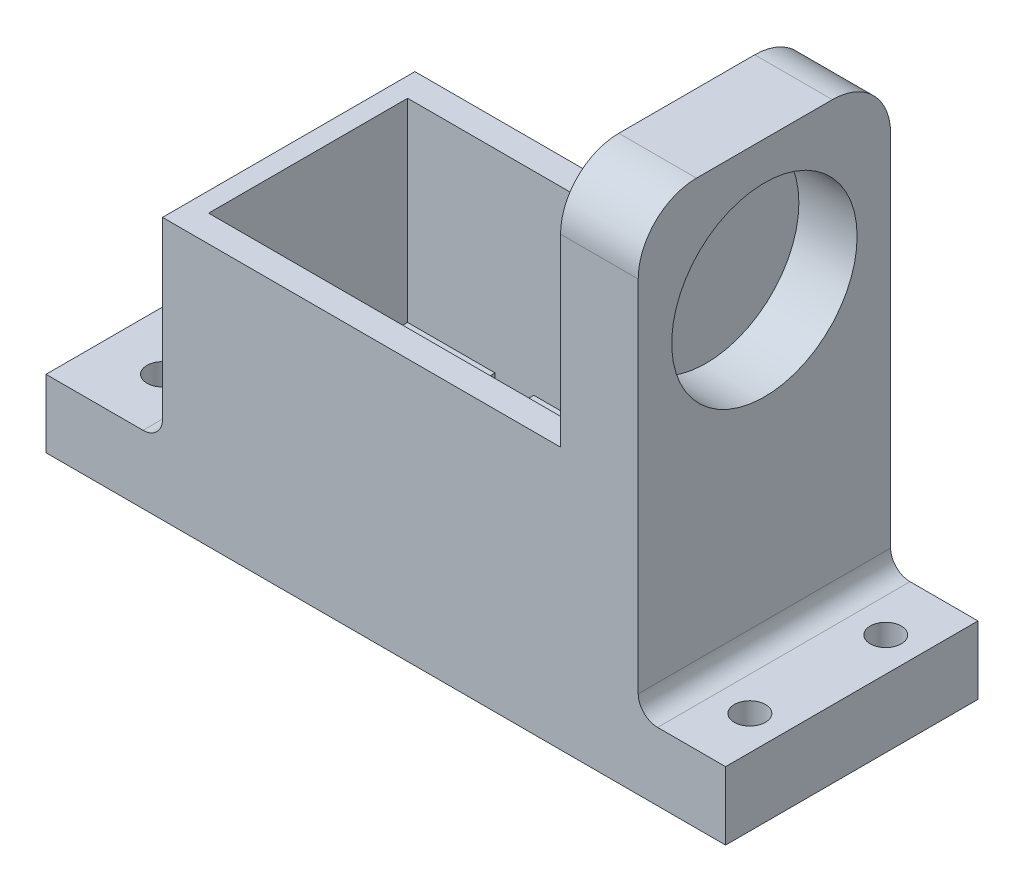
SolidWorks part; units mm, degrees
ref_plane "Plan de face" through (0, 0, 0) normal (0, 0, 1) x (1, 0, 0)
ref_plane "Plan de dessus" through (0, 0, 0) normal (0, 1, 0) x (1, 0, 0)
ref_plane "Plan de droite" through (0, 0, 0) normal (1, 0, 0) x (0, 0, -1)
sketch "Esquisse1" plane through (0, 0, 0) normal (0, 1, 0) x (1, 0, 0)
  line L0 (0, 0) -> (0, 26)
  line L1 (0, 26) -> (70, 26)
  line L2 (70, 26) -> (70, 0)
  line L3 (70, 0) -> (0, 0)
  dimension "D1" = 26
  dimension "D2" = 70
extrude "Boss.-Extru.1" add sketch "Esquisse1" along normal blind 7
sketch "Esquisse2" plane through (0, 7, 0) normal (0, 1, 0) x (1, 0, 0)
  line L0 (53, 26) -> (53, 0)
  line L1 (70, 26) -> (0, 26) construction
  line L2 (0, 0) -> (70, 0) construction
  line L3 (53, 0) -> (61, 0)
  line L4 (61, 0) -> (61, 26)
  line L5 (61, 26) -> (53, 26)
  dimension "D1" = 9
  dimension "D2" = 8
extrude "Boss.-Extru.2" add sketch "Esquisse2" along normal blind 45
sketch "Esquisse3" plane through (0, 7, 0) normal (0, 1, 0) x (1, 0, 0)
  line L0 (53, 26) -> (12, 26)
  line L1 (53, 26) -> (0, 26) construction
  line L2 (12, 26) -> (12, 0)
  line L3 (0, 0) -> (53, 0) construction
  line L4 (12, 0) -> (53, 0)
  line L5 (53, 26) -> (53, 23.25)
  line L6 (53, 23.25) -> (14, 23.25)
  line L7 (14, 23.25) -> (14, 2.75)
  line L8 (14, 2.75) -> (53, 2.75)
  line L9 (53, 2.75) -> (53, 0)
  dimension "D1" = 2
  dimension "D2" = 2.75
  dimension "D3" = 2.75
  dimension "D4" = 41
extrude "Boss.-Extru.3" add sketch "Esquisse3" along normal blind 20
sketch "Esquisse4" plane through (0, 7, 0) normal (0, 1, 0) x (1, 0, 0)
  line L0 (23, 23.25) -> (23, 2.75)
  line L1 (14, 23.25) -> (53, 23.25) construction
  line L2 (53, 2.75) -> (14, 2.75) construction
  line L3 (23, 2.75) -> (27, 2.75)
  line L4 (53, 2.75) -> (14, 2.75) construction
  line L5 (27, 2.75) -> (27, 23.25)
  line L6 (27, 23.25) -> (23, 23.25)
  dimension "D1" = 4
  dimension "D2" = 9
extrude "Enlèv. mat.-Extru.1" cut sketch "Esquisse4" against normal up to next
fillet "Congé1" radius 1 1 edges
fillet "Congé2" radius 2 2 edges at (12, 7, -13)
sketch "Esquisse5" plane through (0, 7, 0) normal (0, 1, 0) x (1, 0, 0)
  line L0 (0, 13) -> (70, 13) construction
  line L1 (0, 26) -> (0, 0) construction
  line L2 (70, 0) -> (70, 26) construction
  circle A0 centre (6, 20) radius 1.6
  circle A1 centre (66.5, 20) radius 1.6
  circle A2 centre (66.5, 6) radius 1.6
  circle A3 centre (6, 6) radius 1.6
  dimension "D1" = 3.2
  dimension "D2" = 3.2
  dimension "D3" = 6
  dimension "D4" = 3.5
  dimension "D5" = 6
  dimension "D6" = 6
extrude "Enlèv. mat.-Extru.2" cut sketch "Esquisse5" against normal up to next
fillet "Congé3" radius 6 2 edges at (57, 52, -26) (57, 52, 0)
sketch "Esquisse6" plane through (61, 0, 0) normal (1, 0, 0) x (0, 0, -1)
  circle A0 centre (13, 38.53) radius 9.55
  dimension "D3" = 19.1
  dimension "D1" = 31.53
  dimension "D2" = 13
extrude "Enlèv. mat.-Extru.3" cut sketch "Esquisse6" against normal blind 6
